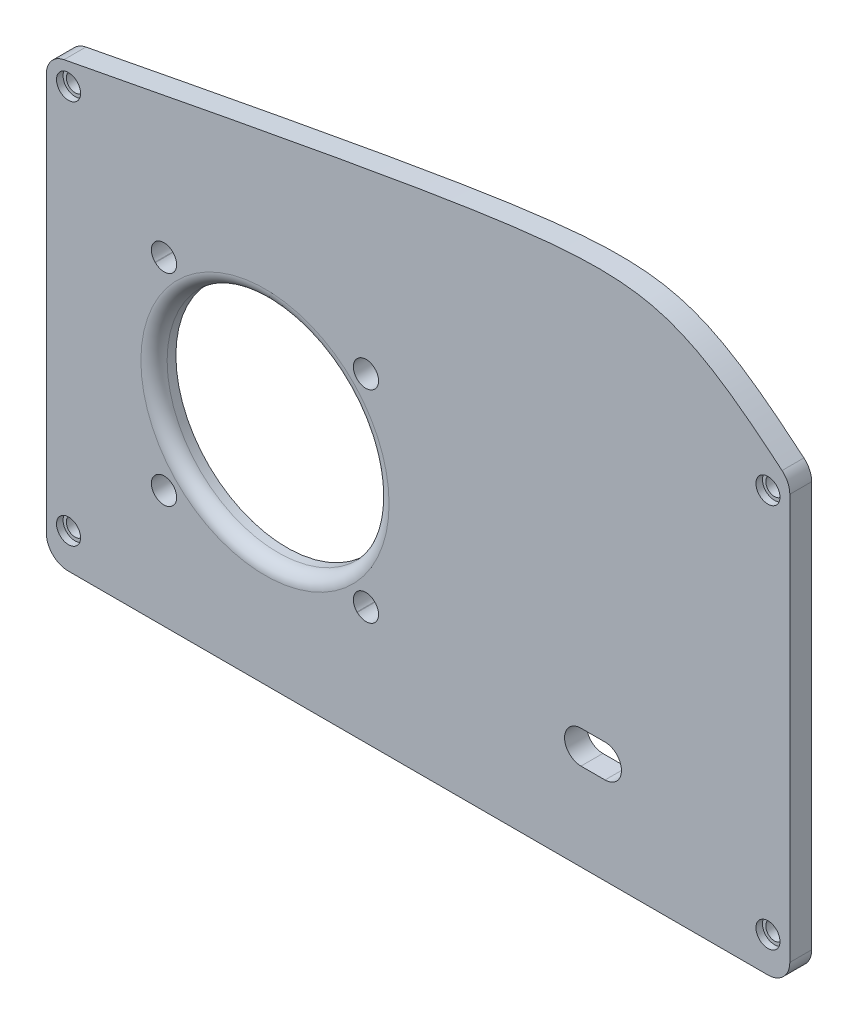
SolidWorks part; units mm, degrees
ref_plane "Plan de face" through (0, 0, 0) normal (0, 0, 1) x (1, 0, 0)
ref_plane "Plan de dessus" through (0, 0, 0) normal (0, 1, 0) x (1, 0, 0)
ref_plane "Plan de droite" through (0, 0, 0) normal (1, 0, 0) x (0, 0, -1)
sketch "Esquisse2" plane through (0, 0, 0) normal (0, 0, 1) x (1, 0, 0)
  line L6 (-23.2224, 101.3099) -> (-23.2224, 1.31)
  line L7 (-23.2224, 1.31) -> (146.7776, 1.31)
  line L8 (146.7776, 1.31) -> (146.7776, 101.3097)
  spline S2 degree 3 poles (146.7776, 101.3097) (145.3783, 102.5087) (143.9696, 103.6962) (141.1249, 106.0382) (139.6886, 107.193) (136.7775, 109.4522) (135.3056, 110.5547) (132.3129, 112.6786) (130.7923, 113.7002) (127.6774, 115.6217) (126.083, 116.5211) (123.6125, 117.7395) (122.7758, 118.1237) (121.0718, 118.8415) (120.2013, 119.1759) (117.5652, 120.0856) (115.7775, 120.5668) (112.1445, 121.2916) (110.2933, 121.5372) (106.5971, 121.84) (104.7475, 121.9004) (101.0462, 121.8978) (99.1945, 121.8347) (95.4896, 121.6271) (93.6392, 121.4821) (89.9478, 121.1385) (88.1055, 120.9397) (82.5856, 120.2872) (78.9148, 119.7795) (71.5822, 118.6915) (67.9202, 118.1096) (56.946, 116.3015) (49.6442, 115.0148) (35.0517, 112.3792) (27.7614, 111.0279) (5.8992, 106.9256) (-8.6635, 104.1276) (-23.2224, 101.3099) knots 0 0 0 0 0.03125 0.03125 0.0625 0.0625 0.09375 0.09375 0.125 0.125 0.15625 0.15625 0.171875 0.171875 0.1875 0.1875 0.21875 0.21875 0.25 0.25 0.28125 0.28125 0.3125 0.3125 0.34375 0.34375 0.375 0.375 0.4375 0.4375 0.5 0.5 0.625 0.625 0.75 0.75 1 1 1 1
extrude "Boss.-Extru.1" add sketch "Esquisse2" along normal blind 5
sketch "Esquisse3" plane through (0, 0, 5) normal (0, 0, 1) x (1, 0, 0)
  line L0 (-18.1424, 97.2922) -> (-11.1424, 97.2922) construction
  line L1 (-18.1424, 97.2922) -> (-18.1424, 91.7922) construction
  line L3 (146.7776, 1.31) -> (146.7776, 101.3097) construction
  line L4 (-18.1424, 97.2922) -> (-18.1424, 102.2922) construction
  line L5 (-18.1424, 97.2922) -> (-23.2224, 97.2922) construction
  line L6 (-23.2224, 101.3099) -> (-23.2224, 1.31) construction
  line L7 (-23.2224, 1.31) -> (146.7776, 1.31) construction
  circle A0 centre (-18.1424, 97.2922) radius 2
  circle A1 centre (-18.1424, 9.31) radius 2
  circle A2 centre (141.7776, 9.31) radius 2
  circle A3 centre (141.7776, 97.2922) radius 2
  spline S0 degree 3 poles (146.7776, 101.3097) (145.3783, 102.5087) (143.9696, 103.6962) (141.1249, 106.0382) (139.6886, 107.193) (136.7775, 109.4522) (135.3056, 110.5547) (132.3129, 112.6786) (130.7923, 113.7002) (127.6774, 115.6217) (126.083, 116.5211) (123.6125, 117.7395) (122.7758, 118.1237) (121.0718, 118.8415) (120.2013, 119.1759) (117.5652, 120.0856) (115.7775, 120.5668) (112.1445, 121.2916) (110.2933, 121.5372) (106.5971, 121.84) (104.7475, 121.9004) (101.0462, 121.8978) (99.1945, 121.8347) (95.4896, 121.6271) (93.6392, 121.4821) (89.9478, 121.1385) (88.1055, 120.9397) (82.5856, 120.2872) (78.9148, 119.7795) (71.5822, 118.6915) (67.9202, 118.1096) (56.946, 116.3015) (49.6442, 115.0148) (35.0517, 112.3792) (27.7614, 111.0279) (5.8992, 106.9256) (-8.6635, 104.1276) (-23.2224, 101.3099) knots 0 0 0 0 0.03125 0.03125 0.0625 0.0625 0.09375 0.09375 0.125 0.125 0.15625 0.15625 0.171875 0.171875 0.1875 0.1875 0.21875 0.21875 0.25 0.25 0.28125 0.28125 0.3125 0.3125 0.34375 0.34375 0.375 0.375 0.4375 0.4375 0.5 0.5 0.625 0.625 0.75 0.75 1 1 1 1 construction
  dimension "D1" = 4
  dimension "D2" = 7
  dimension "D3" = 5.5
  dimension "D4" = 5.08
  dimension "D5" = 8
  dimension "D6" = 5
  dimension "D7" = 5
  dimension "D8" = 5
  dimension "D9" = 8
extrude "Enlèv. mat.-Extru.1" cut sketch "Esquisse3" against normal blind 5
sketch "Esquisse4" plane through (0, 0, 5) normal (0, 0, 1) x (1, 0, 0)
  circle A0 centre (-18.1424, 97.2922) radius 2.75
  circle A1 centre (141.7776, 97.2922) radius 2.75
  circle A2 centre (-18.1424, 9.31) radius 2.75
  circle A3 centre (141.7776, 9.31) radius 2.75
  dimension "D1" = 5.5
  dimension "D2" = 5.5
  dimension "D3" = 5.5
  dimension "D4" = 5.5
extrude "Enlèv. mat.-Extru.2" cut sketch "Esquisse4" against normal blind 1.5
sketch "Esquisse5" plane through (0, 0, 5) normal (0, 0, 1) x (1, 0, 0)
  line L0 (-23.2224, 101.3099) -> (-23.2224, 1.31) construction
  line L1 (-23.2224, 1.31) -> (146.7776, 1.31) construction
  circle A0 centre (26.7776, 51.31) radius 25.375
  dimension "D1" = 50.75
  dimension "D2" = 50
  dimension "D3" = 50
extrude "Enlèv. mat.-Extru.3" cut sketch "Esquisse5" against normal blind 12.5 and the other way blind 5
fillet "Congé1" radius 3 1 edges at (1.4026, 51.31, 5)
fillet "Congé2" radius 5 4 edges at (146.7776, 1.31, 2.5) (-23.2224, 1.31, 2.5)
sketch "Esquisse6" plane through (0, 0, 5) normal (0, 0, 1) x (1, 0, 0)
  line L0 (3.7259, 74.3617) -> (3.6552, 74.4324) construction
  line L1 (5.7411, 76.3769) -> (5.6704, 76.4476)
  line L2 (1.7106, 72.3464) -> (1.6399, 72.4171)
  line L3 (26.7776, 51.31) -> (-5.5936, 83.6811) construction
  line L4 (26.7776, 51.31) -> (6.8297, 51.31) construction
  line L5 (26.7776, 76.685) -> (26.7776, 66.9345) construction
  line L6 (52.1526, 51.31) -> (40.7895, 51.31) construction
  line L7 (49.8292, 74.3617) -> (49.9, 74.4324) construction
  line L8 (47.814, 76.3769) -> (47.8847, 76.4476)
  line L9 (51.8445, 72.3464) -> (51.9152, 72.4171)
  line L10 (49.8292, 28.2583) -> (49.9, 28.1876) construction
  line L11 (47.814, 26.2431) -> (47.8847, 26.1724)
  line L12 (51.8445, 30.2736) -> (51.9152, 30.2029)
  line L13 (3.7259, 28.2583) -> (3.6552, 28.1876) construction
  line L14 (5.7411, 26.2431) -> (5.6704, 26.1724)
  line L15 (1.7106, 30.2736) -> (1.6399, 30.2029)
  arc A0 (5.7411, 76.3769) -> (1.7106, 72.3464) centre (3.7259, 74.3617) cw
  arc A1 (1.6399, 72.4171) -> (5.6704, 76.4476) centre (3.6552, 74.4324) cw
  circle A2 centre (26.7776, 51.31) radius 25.375 construction
  arc A3 (47.814, 76.3769) -> (51.8445, 72.3464) centre (49.8292, 74.3617) ccw
  arc A4 (51.9152, 72.4171) -> (47.8847, 76.4476) centre (49.9, 74.4324) ccw
  arc A5 (47.814, 26.2431) -> (51.8445, 30.2736) centre (49.8292, 28.2583) cw
  arc A6 (51.9152, 30.2029) -> (47.8847, 26.1724) centre (49.9, 28.1876) cw
  arc A7 (5.7411, 26.2431) -> (1.7106, 30.2736) centre (3.7259, 28.2583) ccw
  arc A8 (1.6399, 30.2029) -> (5.6704, 26.1724) centre (3.6552, 28.1876) ccw
  point P2 (3.6905, 74.397)
  point P7 (5.7411, 72.3464)
  point P13 (1.6399, 76.4476)
  point P21 (49.8646, 74.397)
  point P28 (49.8646, 28.223)
  point P35 (3.6905, 28.223)
  dimension "D1" = 29.75
  dimension "D5" = 5.8
  dimension "D3" = 5.7
  dimension "D2" = 45
extrude "Enlèv. mat.-Extru.4" cut sketch "Esquisse6" against normal blind 10
sketch "Esquisse7" plane through (0, 0, 5) normal (0, 0, 1) x (1, 0, 0)
  line L0 (99.0276, 25.06) -> (104.5276, 25.06) construction
  line L1 (99.0276, 28.81) -> (104.5276, 28.81)
  line L2 (99.0276, 21.31) -> (104.5276, 21.31)
  line L3 (-18.2224, 1.31) -> (141.7776, 1.31) construction
  line L4 (146.7776, 6.31) -> (146.7776, 98.9987) construction
  arc A0 (99.0276, 28.81) -> (99.0276, 21.31) centre (99.0276, 25.06) ccw
  arc A1 (104.5276, 21.31) -> (104.5276, 28.81) centre (104.5276, 25.06) ccw
  point P2 (101.7776, 25.06)
  point P7 (95.2776, 25.06)
  point P8 (108.2776, 25.06)
  dimension "D1" = 13
  dimension "D2" = 7.5
  dimension "D3" = 20
  dimension "D4" = 45
extrude "Enlèv. mat.-Extru.5" cut sketch "Esquisse7" against normal blind 10
